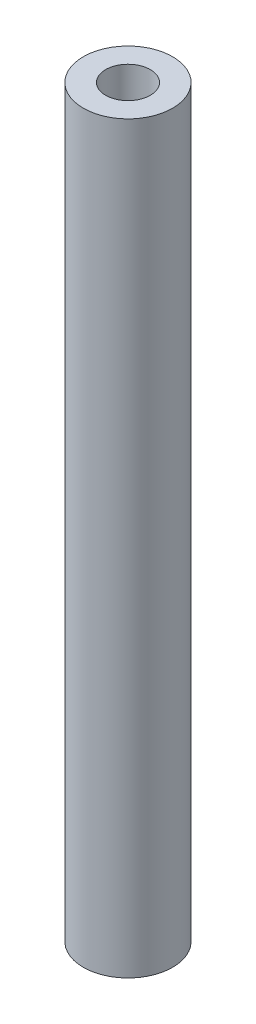
SolidWorks part; units mm, degrees
material "Hexcel AS4C (3000 丝)"
ref_plane "前视基准面" through (0, 0, 0) normal (0, 0, 1) x (1, 0, 0)
ref_plane "上视基准面" through (0, 0, 0) normal (0, 1, 0) x (1, 0, 0)
ref_plane "右视基准面" through (0, 0, 0) normal (1, 0, 0) x (0, 0, -1)
other "Configuration Table"
sketch "草图1" plane through (0, 0, 0) normal (0, 1, 0) x (1, 0, 0)
  circle A0 centre (0, 0) radius 3
  circle A1 centre (0, 0) radius 1.5
  dimension "D1" = 6
  dimension "D2" = 3
extrude "凸台-拉伸1" add sketch "草图1" along normal blind 50
